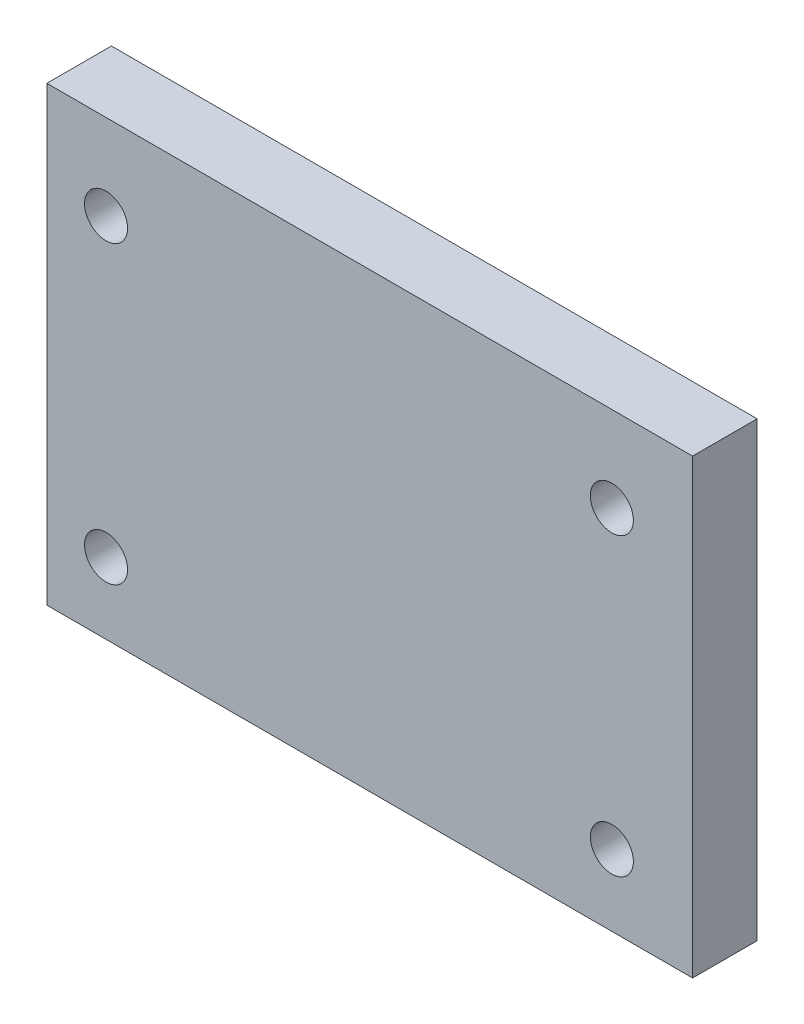
SolidWorks part; units mm, degrees
ref_plane "Plan de face" through (0, 0, 0) normal (0, 0, 1) x (1, 0, 0)
ref_plane "Plan de dessus" through (0, 0, 0) normal (0, 1, 0) x (1, 0, 0)
ref_plane "Plan de droite" through (0, 0, 0) normal (1, 0, 0) x (0, 0, -1)
sketch "Esquisse1" plane through (0, 0, 0) normal (0, 0, 1) x (1, 0, 0)
  line L1 (0, 0) -> (300, 0)
  line L2 (0, 0) -> (0, 210)
  line L3 (0, 210) -> (300, 210)
  line L4 (300, 0) -> (300, 210)
  dimension "D1" = 300
  dimension "D2" = 210
extrude "Boss.-Extru.1" add sketch "Esquisse1" along normal blind 30
sketch "Esquisse2" plane through (0, 0, 0) normal (0, 0, -1) x (-1, 0, 0)
  circle A0 centre (-27.5, 33.0559) radius 10
  circle A1 centre (-27.5, 170.3559) radius 10
  circle A2 centre (-262.5, 170.3559) radius 10
  circle A3 centre (-262.5, 33.0559) radius 10
extrude "Enlèv. mat.-Extru.1" cut sketch "Esquisse2" against normal blind 30
